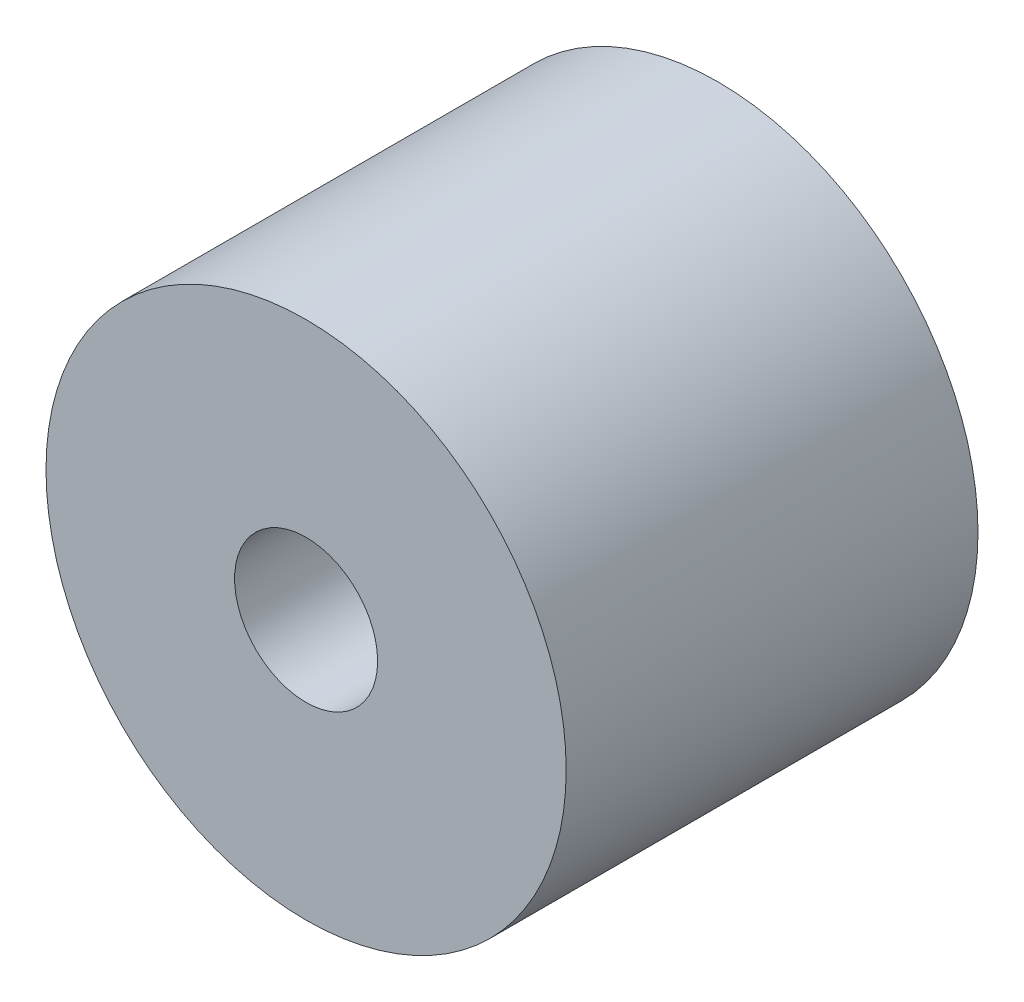
SolidWorks part; units mm, degrees
ref_plane "前视基准面" through (0, 0, 0) normal (0, 0, 1) x (1, 0, 0)
ref_plane "上视基准面" through (0, 0, 0) normal (0, 1, 0) x (1, 0, 0)
ref_plane "右视基准面" through (0, 0, 0) normal (1, 0, 0) x (0, 0, -1)
other "Configuration Table"
sketch "草图1" plane through (0, 0, 0) normal (0, 0, 1) x (1, 0, 0)
  circle A0 centre (0, 0) radius 1.65
  circle A1 centre (0, 0) radius 6
  dimension "D1" = 3.3
  dimension "D2" = 12
extrude "凸台-拉伸1" add sketch "草图1" along normal blind 9.5
